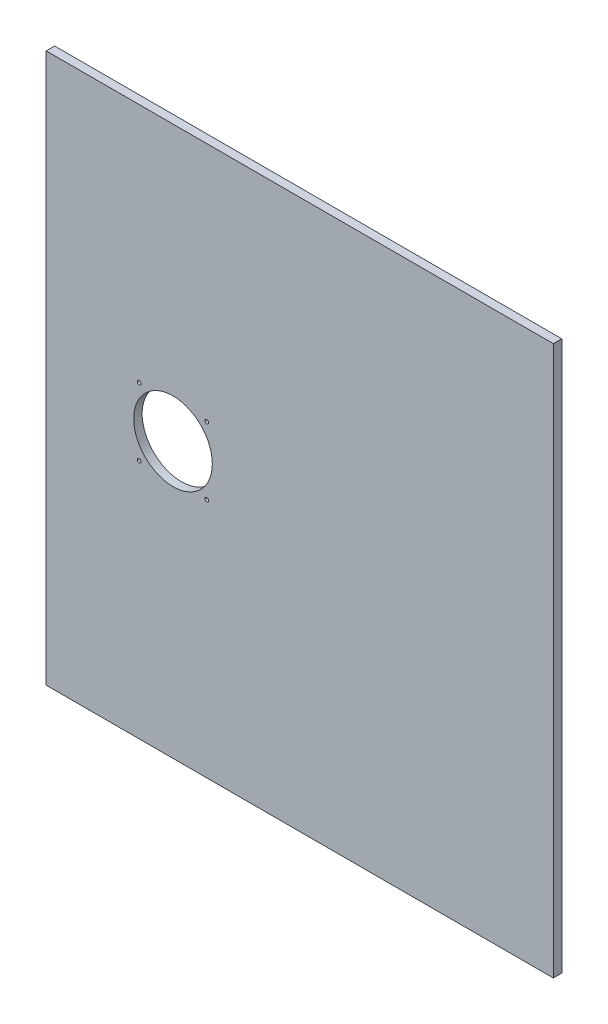
SolidWorks part; units mm, degrees
ref_plane "Plan de face" through (0, 0, 0) normal (0, 0, 1) x (1, 0, 0)
ref_plane "Plan de dessus" through (0, 0, 0) normal (0, 1, 0) x (1, 0, 0)
ref_plane "Plan de droite" through (0, 0, 0) normal (1, 0, 0) x (0, 0, -1)
sketch "Esquisse1" plane through (0, 0, 0) normal (0, 0, 1) x (1, 0, 0)
  line L1 (0, 0) -> (600, 0)
  line L2 (0, 0) -> (0, -650)
  line L3 (0, -650) -> (600, -650)
  line L4 (600, 0) -> (600, -650)
  dimension "D1" = 600
  dimension "D2" = 650
extrude "Boss.-Extru.1" add sketch "Esquisse1" along normal blind 10
sketch "Esquisse2" plane through (0, 0, 10) normal (0, 0, 1) x (1, 0, 0)
  line L1 (0, 0) -> (0, -650) construction
  circle A0 centre (150, -325) radius 46.5
  circle A1 centre (110, -285) radius 2.25
  circle A2 centre (190, -285) radius 2.25
  circle A3 centre (190, -365) radius 2.25
  circle A4 centre (110, -365) radius 2.25
  point P12 (0, -325)
  dimension "D1" = 4.5
  dimension "D2" = 4.5
  dimension "D3" = 4.5
  dimension "D4" = 4.5
  dimension "D5" = 93
  dimension "D10" = 80
  dimension "D6" = 80
  dimension "D7" = 80
  dimension "D8" = 80
  dimension "D9" = 80
  dimension "D11" = 80
  dimension "D12" = 0
  dimension "D13" = 40
  dimension "D14" = 40
  dimension "D15" = 150
extrude "Enlèv. mat.-Extru.1" cut sketch "Esquisse2" against normal blind 10
